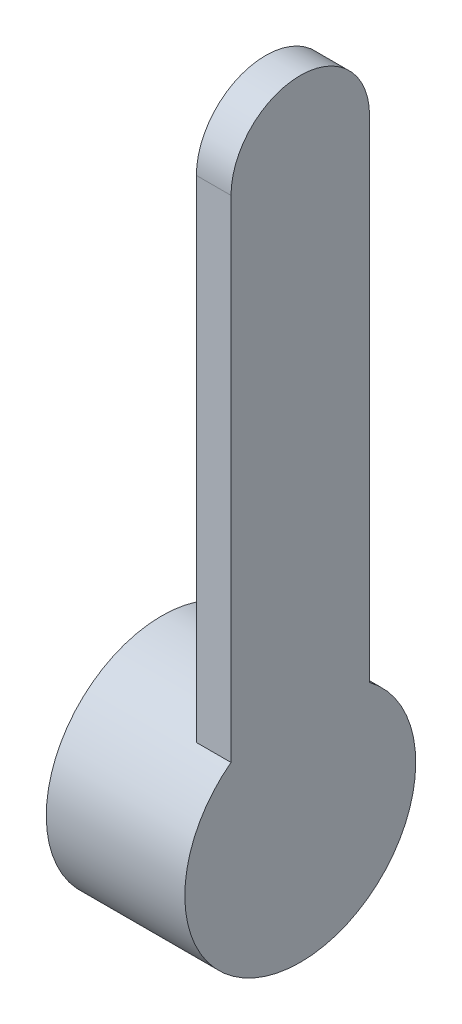
SolidWorks part; units mm, degrees
ref_plane "Front Plane" through (0, 0, 0) normal (0, 0, 1) x (1, 0, 0)
ref_plane "Top Plane" through (0, 0, 0) normal (0, 1, 0) x (1, 0, 0)
ref_plane "Right Plane" through (0, 0, 0) normal (1, 0, 0) x (0, 0, -1)
sketch "Sketch1" plane through (0, 0, 0) normal (1, 0, 0) x (0, 0, -1)
  circle A0 centre (0, 0) radius 1.5
  circle A1 centre (0, 0) radius 2.5
  dimension "D1" = 3
  dimension "D2" = 1
extrude "Boss-Extrude1" add sketch "Sketch1" along normal blind 3
sketch "Sketch2" plane through (3, 0, 0) normal (1, 0, 0) x (0, 0, -1)
  line L0 (-1.5, 2) -> (-1.5, 12.6328)
  line L1 (0, 0) -> (0, 12.6328) construction
  line L2 (1.5, 2) -> (1.5, 12.6328)
  circle A0 centre (0, 0) radius 2.5 construction
  arc A1 (-1.5, 12.6328) -> (1.5, 12.6328) centre (0, 12.6328) cw
  arc A2 (-1.5, 2) -> (1.5, 2) centre (0, 0) ccw
  dimension "D1" = 1.5
extrude "Boss-Extrude2" add sketch "Sketch2" against normal blind 0.75 contours L0 A1 L2 A2
